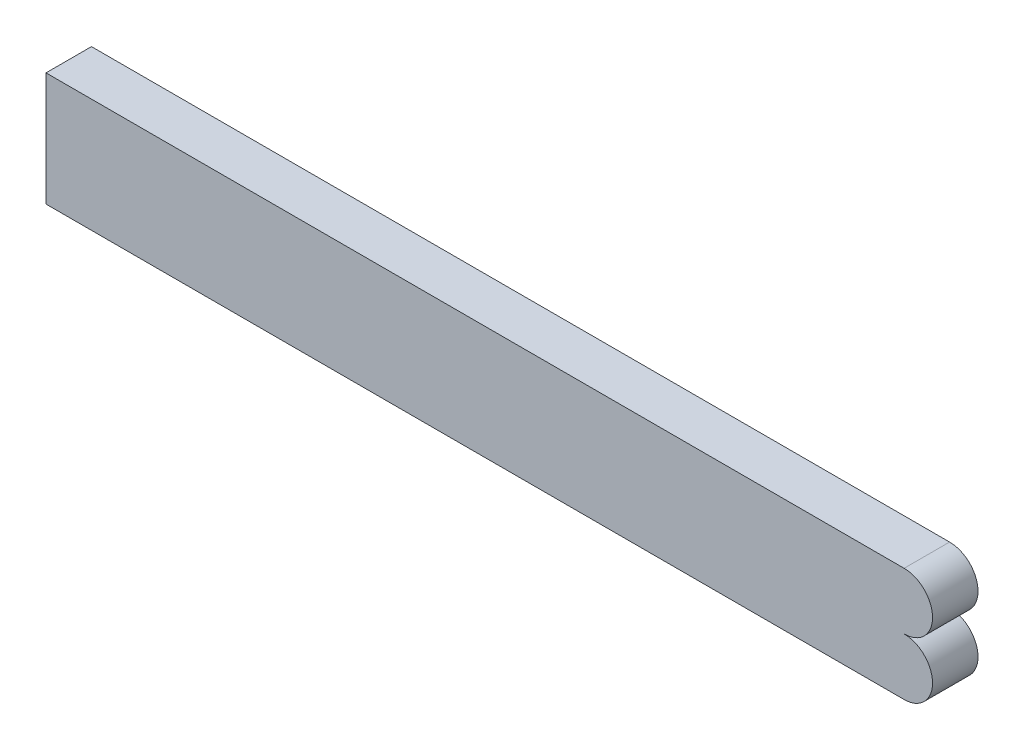
SolidWorks part; units mm, degrees
material "7075-T6 (SN)"
ref_plane "前视基准面" through (0, 0, 0) normal (0, 0, 1) x (1, 0, 0)
ref_plane "上视基准面" through (0, 0, 0) normal (0, 1, 0) x (1, 0, 0)
ref_plane "右视基准面" through (0, 0, 0) normal (1, 0, 0) x (0, 0, -1)
sketch "草图1" plane through (0, 0, 0) normal (0, 0, 1) x (1, 0, 0)
  line L1 (133.0737, -68.764) -> (160.1415, -68.764)
  line L2 (133.0737, -68.764) -> (133.0737, -73.764)
  line L3 (133.0737, -73.764) -> (160.1415, -73.764)
  line L4 (160.1415, -68.764) -> (160.1415, -73.764)
  line L5 (160.1415, -73.764) -> (170.8211, -73.764)
  line L6 (160.1415, -73.764) -> (160.1415, -68.764)
  line L7 (160.1415, -68.764) -> (170.8211, -68.764)
  line L8 (170.8211, -73.764) -> (170.8211, -68.764)
extrude "凸台-拉伸1" add sketch "草图1" along normal blind 2 contours L5 L8 L7 L4 | L4 L1 L2 L3
sketch "草图2" plane through (0, 0, 2) normal (0, 0, 1) x (1, 0, 0)
  line L0 (170.8211, -71.264) -> (170.8211, -68.764)
  line L1 (170.8211, -73.764) -> (170.8211, -68.764) construction
  line L2 (170.8211, -71.264) -> (170.8211, -73.764)
  circle A0 centre (170.8211, -70.014) radius 1.25
  circle A1 centre (170.8211, -72.514) radius 1.25
  line M2 (170.8211, -73.764) -> (170.8211, -68.764)
extrude "凸台-拉伸2" add sketch "草图2" against normal blind 2 contours A0 M2 | A1 M2
